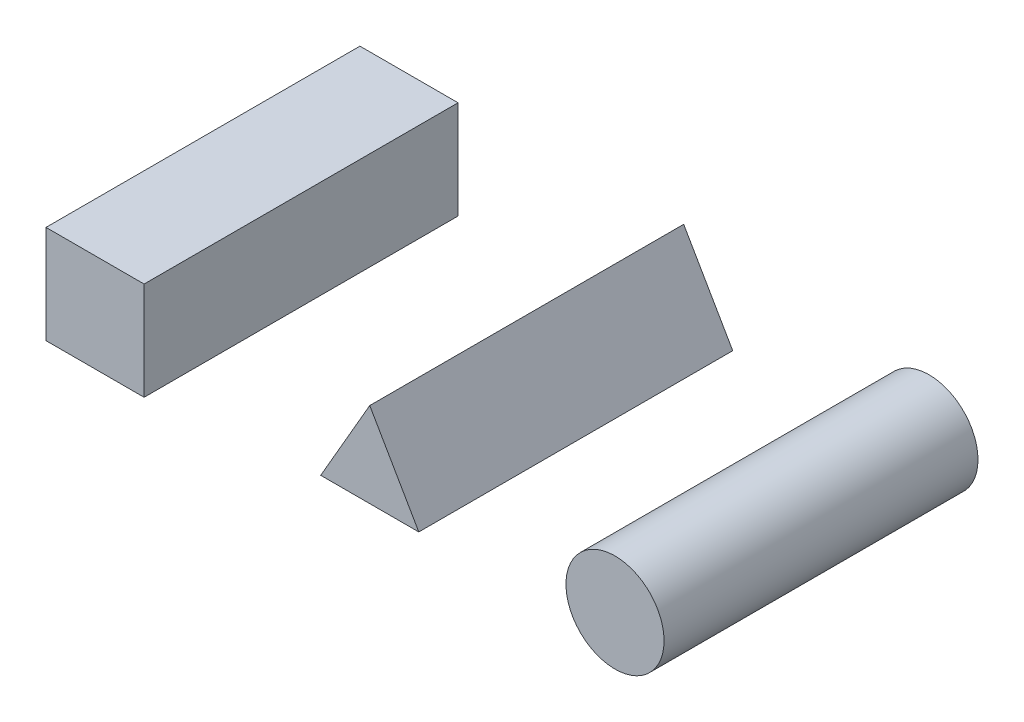
SolidWorks part; units mm, degrees
ref_plane "Front Plane" through (0, 0, 0) normal (0, 0, 1) x (1, 0, 0)
ref_plane "Top Plane" through (0, 0, 0) normal (0, 1, 0) x (1, 0, 0)
ref_plane "Right Plane" through (0, 0, 0) normal (1, 0, 0) x (0, 0, -1)
sketch "Sketch1" plane through (0, 0, 0) normal (0, 0, 1) x (1, 0, 0)
  line L0 (-112.5, 0) -> (112.5, 0) construction
  line L1 (-112.5, 50) -> (112.5, 50)
  line L2 (-112.5, 50) -> (-112.5, -50)
  line L3 (-112.5, -50) -> (112.5, -50)
  line L4 (112.5, 50) -> (112.5, -50)
  line L5 (0, 50) -> (0, -50) construction
  line L6 (-12.5, -7.2169) -> (0, 14.4338)
  line L7 (-82.5, 12.5) -> (-57.5, 12.5)
  line L8 (-82.5, 12.5) -> (-82.5, -12.5)
  line L9 (-82.5, -12.5) -> (-57.5, -12.5)
  line L10 (-57.5, 12.5) -> (-57.5, -12.5)
  line L11 (-82.5, 12.5) -> (-57.5, -12.5) construction
  line L12 (-82.5, -12.5) -> (-57.5, 12.5) construction
  line L14 (-1.3522, 0) -> (0, -1.3522)
  line L18 (0, 14.4338) -> (12.5, -7.2169)
  line L19 (12.5, -7.2169) -> (-12.5, -7.2169)
  line L20 (-12.5, -7.2169) -> (6.25, 3.6084) construction
  line L21 (12.5, -7.2169) -> (-6.25, 3.6084) construction
  line L22 (0, 14.4338) -> (0, 0) construction
  circle A0 centre (62.5, 0) radius 12.5
  point P10 (-70, 0)
  point P20 (0, 0)
  point P27 (7.7505, -5.3087)
  point P28 (0, 0)
  dimension "D2" = 50
  dimension "cylinder" = 25
  dimension "D1" = 30
  dimension "square2" = 25
  dimension "square" = 25
  dimension "triangle3" = 25
  dimension "triangle2" = 25
  dimension "triangle" = 25
extrude "Boss-Extrude1" add sketch "Sketch1" along normal blind 80
